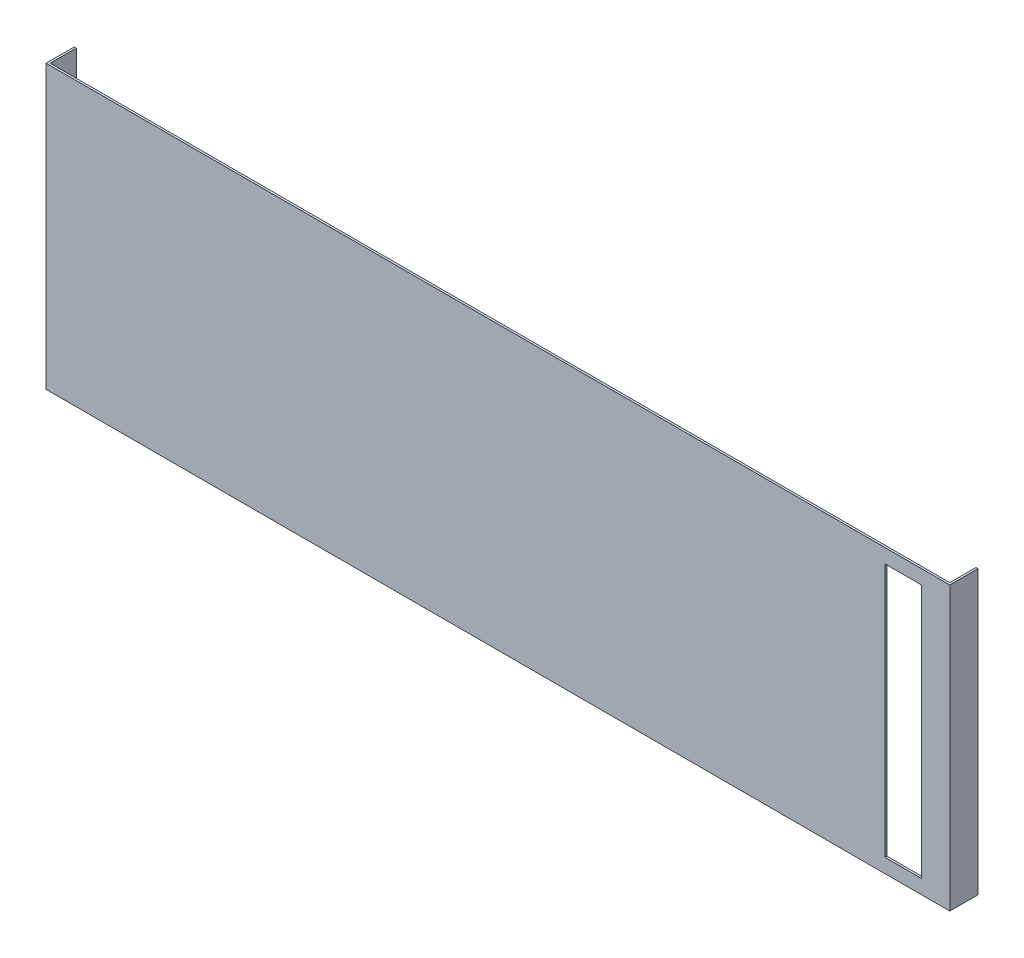
SolidWorks part; units mm, degrees
ref_plane "Front Plane" through (0, 0, 0) normal (0, 0, 1) x (1, 0, 0)
ref_plane "Top Plane" through (0, 0, 0) normal (0, 1, 0) x (1, 0, 0)
ref_plane "Right Plane" through (0, 0, 0) normal (1, 0, 0) x (0, 0, -1)
other "Configuration Table"
sketch "Sketch1" plane through (0, 0, 0) normal (0, 1, 0) x (1, 0, 0)
  line L0 (30, -40) -> (30, -20)
  line L1 (30, -20) -> (31.5, -20)
  line L2 (31.5, -20) -> (31.5, -38.5)
  line L3 (31.5, -38.5) -> (668.5, -38.5)
  line L4 (668.5, -38.5) -> (668.5, -20)
  line L5 (668.5, -20) -> (670, -20)
  line L6 (670, -20) -> (670, -40)
  line L7 (670, -40) -> (30, -40)
extrude "OVEN_pano_kapagi_kapak_1" add sketch "Sketch1" along normal blind 200 from offset 120 separate body
sketch "Sketch2" plane through (0, 0, 0) normal (0, 0, 1) x (1, 0, 0)
  line L1 (624, 130) -> (650, 130)
  line L2 (624, 130) -> (624, 310)
  line L3 (624, 310) -> (650, 310)
  line L4 (650, 130) -> (650, 310)
extrude "OVEN_pano_kapagi_kapak_2" cut sketch "Sketch2" along normal blind 14 from offset 27
